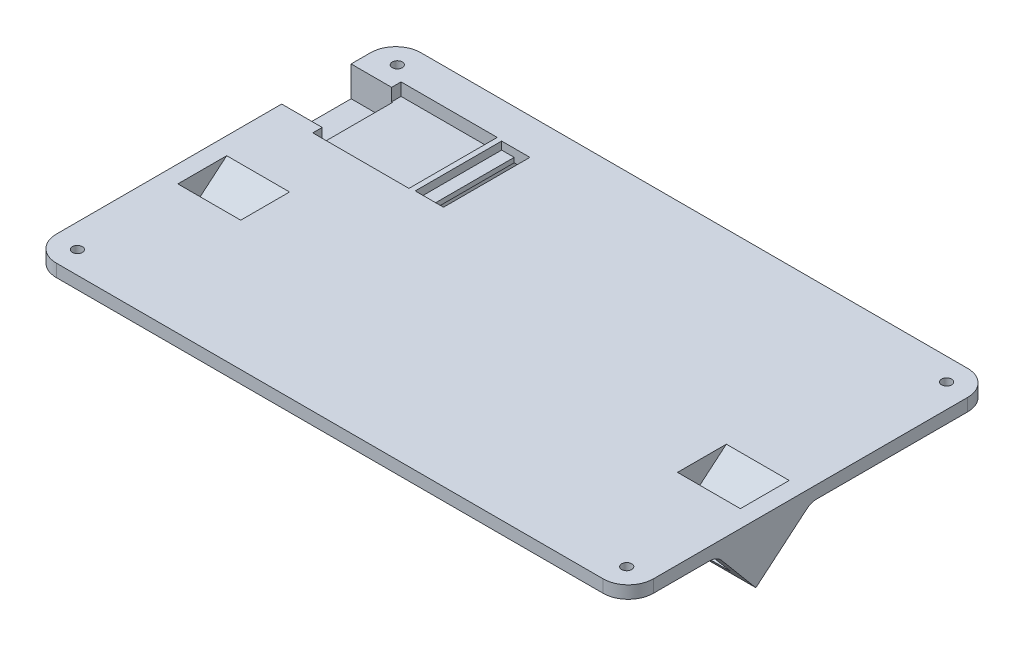
SolidWorks part; units mm, degrees
ref_plane "前视基准面" through (0, 0, 0) normal (0, 0, 1) x (1, 0, 0)
ref_plane "上视基准面" through (0, 0, 0) normal (0, 1, 0) x (1, 0, 0)
ref_plane "右视基准面" through (0, 0, 0) normal (1, 0, 0) x (0, 0, -1)
other "Configuration Table"
sketch "草图1" plane through (0, 0, 0) normal (0, 1, 0) x (1, 0, 0)
  line L1 (-136.2665, -68.2938) -> (136.2665, -68.2938)
  line L2 (-136.2665, -68.2938) -> (-136.2665, 68.2938)
  line L3 (-136.2665, 68.2938) -> (136.2665, 68.2938)
  line L4 (136.2665, -68.2938) -> (136.2665, 68.2938)
  line L5 (-136.2665, -68.2938) -> (136.2665, 68.2938) construction
  line L6 (-136.2665, 68.2938) -> (136.2665, -68.2938) construction
  point P0 (0, 0)
extrude "凸台-拉伸1" add sketch "草图1" along normal blind 4
sketch "草图2" plane through (0, 4, 0) normal (0, 1, 0) x (1, 0, 0)
  line L4 (-87, 58) -> (87, 58) construction
  line L5 (-87, 58) -> (87, 58)
  line L6 (-95, 50) -> (-95, -50)
  line L7 (-87, -58) -> (87, -58)
  line L8 (95, 50) -> (95, -50)
  line L9 (-95, -50) -> (-95, 50) construction
  line L10 (-87, -58) -> (87, -58) construction
  line L11 (95, -50) -> (95, 50) construction
  line L13 (-136.2665, 68.2938) -> (136.2665, 68.2938)
  line L14 (-136.2665, 68.2938) -> (-136.2665, -68.2938)
  line L15 (-136.2665, -68.2938) -> (136.2665, -68.2938)
  line L16 (136.2665, 68.2938) -> (136.2665, -68.2938)
  arc A0 (87, 58) -> (95, 50) centre (87, 50) cw
  arc A1 (-95, -50) -> (-87, -58) centre (-87, -50) ccw
  arc A2 (87, -58) -> (95, -50) centre (87, -50) ccw
  arc A3 (-87, 58) -> (-95, 50) centre (-87, 50) ccw
  dimension "D1" = 8
extrude "切除-拉伸1" cut sketch "草图2" against normal blind 4
sketch "草图3" plane through (0, 0, 0) normal (0, -1, 0) x (1, 0, 0)
  line L0 (-95, -22) -> (-81.8, -22)
  line L1 (-81.8, -22) -> (-81.8, -19)
  line L2 (-81.8, -19) -> (-51.8, -19)
  line L3 (-51.8, -19) -> (-81.8, -19) construction
  line L4 (-51.8, -19) -> (-51.8, -46.5)
  line L5 (-51.8, -46.5) -> (-51.8, -19) construction
  line L6 (-51.8, -46.5) -> (-81.8, -46.5)
  line L7 (-81.8, -46.5) -> (-81.8, -43.5)
  line L8 (-81.8, -43.5) -> (-81.8, -46.5) construction
  line L9 (-81.8, -43.5) -> (-81.8, -22) construction
  line L10 (-81.8, -43.5) -> (-95, -43.5)
  line L11 (-95, -43.5) -> (-95, -22)
extrude "切除-拉伸2" cut sketch "草图3" against normal blind 4
sketch "草图4" plane through (0, 0, 0) normal (0, -1, 0) x (1, 0, 0)
  line L0 (-95, -32.75) -> (-24.4506, -32.75) construction
  line L1 (-95, -43.5) -> (-95, -22) construction
  line L2 (-51.5, -18.7) -> (-51.5, -46.8)
  line L3 (-95, -21.7) -> (-95, -43.8)
  line L4 (-95, -22) -> (-81.8, -22) construction
  line L5 (-81.8, -22) -> (-81.8, -19) construction
  line L6 (-81.8, -19) -> (-51.8, -19) construction
  line L7 (-51.8, -19) -> (-51.8, -46.5) construction
  line L8 (-82.1, -46.8) -> (-51.5, -46.8)
  line L9 (-82.1, -43.8) -> (-82.1, -46.8)
  line L10 (-95, -43.8) -> (-82.1, -43.8)
  line L25 (-95, -21.7) -> (-82.1, -21.7)
  line L26 (-95, -22) -> (-95, 50) construction
  line L27 (-82.1, -21.7) -> (-82.1, -18.7)
  line L28 (-82.1, -18.7) -> (-51.5, -18.7)
  point P19 (-51.5, -32.75)
  dimension "D1" = 0.3
  dimension "D2" = 0.3
  dimension "D3" = 0.3
  dimension "D4" = 0.3
extrude "切除-拉伸3" cut sketch "草图4" against normal blind 4 contours L28 L2 L8 L9 L10 L3 L25 L27
sketch "草图5" plane through (0, 0, 0) normal (0, -1, 0) x (1, 0, 0)
  line L0 (-81.8, -43.5) -> (-81.8, -22) construction
  line L1 (-47.8, -50.75) -> (-81.8, -50.75)
  line L2 (-47.8, -50.75) -> (-47.8, -14.75)
  line L3 (-47.8, -14.75) -> (-81.8, -14.75)
  line L4 (-81.8, -50.75) -> (-81.8, -14.75)
  line L5 (-47.8, -50.75) -> (-81.8, -14.75) construction
  line L6 (-47.8, -14.75) -> (-81.8, -50.75) construction
  line L7 (-95, -32.75) -> (-25.646, -32.75) construction
  line L8 (-95, -22) -> (-95, -43.5) construction
  line L9 (-51.8, -46.5) -> (-51.8, -19) construction
  point P0 (-64.8, -32.75)
  dimension "D1" = 36
  dimension "D2" = 4
extrude "凸台-拉伸2" add sketch "草图5" along normal blind 4 contours L3 L4 L1 L2
sketch "草图6" plane through (0, 0, 0) normal (0, -1, 0) x (1, 0, 0)
  line L0 (-81.8, -18.7) -> (-81.8, -14.75) construction
  line L9 (-95, -21.7) -> (-81.8, -21.7)
  line L10 (-95, -21.7) -> (-95, -17.7)
  line L11 (-95, -17.7) -> (-81.8, -17.7)
  line L12 (-81.8, -21.7) -> (-81.8, -17.7)
  line L13 (-81.8, -50.75) -> (-81.8, -46.8) construction
  line L14 (-95, -43.8) -> (-81.8, -43.8)
  line L15 (-95, -43.8) -> (-95, -47.8)
  line L16 (-95, -47.8) -> (-81.8, -47.8)
  line L17 (-81.8, -43.8) -> (-81.8, -47.8)
  dimension "D1" = 4
  dimension "D2" = 4
extrude "凸台-拉伸3" add sketch "草图6" along normal blind 5.6
sketch "草图7" plane through (0, -5.6, 0) normal (0, -1, 0) x (1, 0, 0)
  line L0 (-95, -47.8) -> (-81.8, -47.8) construction
  line L5 (-95, -17.7) -> (-77.8, -17.7)
  line L6 (-95, -17.7) -> (-95, -47.8)
  line L7 (-95, -47.8) -> (-77.8, -47.8)
  line L8 (-77.8, -17.7) -> (-77.8, -47.8)
  line L9 (-81.8, -43.5) -> (-81.8, -22) construction
  dimension "D1" = 4
extrude "凸台-拉伸4" add sketch "草图7" along normal blind 4
sketch "草图8" plane through (0, 4, 0) normal (0, 1, 0) x (1, 0, 0)
  line L1 (-81.8, 19) -> (-45.8, 19) construction
  line L2 (-45.8, 46.5) -> (-40.8, 46.5)
  line L3 (-45.8, 46.5) -> (-45.8, 19)
  line L4 (-45.8, 19) -> (-40.8, 19)
  line L5 (-40.8, 46.5) -> (-40.8, 19)
  dimension "D1" = 5
extrude "切除-拉伸4" cut sketch "草图8" against normal blind 4
sketch "草图9" plane through (-45.8, 0, 0) normal (1, 0, 0) x (0, 0, -1)
  line L0 (19, -0.1) -> (19, 6.4) construction
  line L1 (19, 4) -> (46.5, 4)
  line L2 (19, 4) -> (19, 1.5)
  line L3 (19, 1.5) -> (46.5, 1.5)
  line L4 (46.5, 4) -> (46.5, 1.5)
  line L5 (7.5, 4) -> (21.5, 4) construction
  line L6 (46.5, 6.4) -> (46.5, 7.9) construction
  dimension "D1" = 2.5
extrude "切除-拉伸5" cut sketch "草图9" against normal blind 4
sketch "草图10" plane through (0, 4, 0) normal (0, 1, 0) x (1, 0, 0)
  circle A0 centre (87.4, 50.9) radius 1.6
  circle A1 centre (-87.4, 50.9) radius 1.6
  circle A2 centre (-87.4, -50.9) radius 1.6
  circle A3 centre (87.4, -50.9) radius 1.6
extrude "切除-拉伸6" cut sketch "草图10" against normal blind 10
sketch "草图11" plane through (95, 0, 0) normal (1, 0, 0) x (0, 0, -1)
  line L0 (0.1985, 0.0243) -> (-29.8015, 0)
  line L1 (-50, 0) -> (50, 0) construction
  line L2 (-29.8015, 0) -> (-17.3942, -14.7621)
  line L3 (0.1985, 0.0243) -> (-17.3942, -14.7621)
  dimension "D1" = 50
  dimension "D2" = 30
  dimension "D3" = 90
  dimension "D4" = 12.4073
extrude "凸台-拉伸5" add sketch "草图11" against normal up to surface (190 mm away) up to face at (-95, -1.2, -21.8333)
sketch "草图13" plane through (0, -14.6785, 17.4644) normal (0, -0.6434, 0.7655) x (1, 0, 0)
  line L0 (95, 19.1745) -> (95, -0.1091) construction
  line L1 (89.5, 3.8909) -> (69.5, 3.8909)
  line L2 (89.5, 3.8909) -> (89.5, 13.8909)
  line L3 (89.5, 13.8909) -> (69.5, 13.8909)
  line L4 (69.5, 3.8909) -> (69.5, 13.8909)
  line L5 (-95, -0.1091) -> (95, -0.1091) construction
  line L6 (-87, 37.3177) -> (87, 37.3177) construction
  line L7 (0, 37.3177) -> (0, 0) construction
  line L8 (-69.5, 3.8909) -> (-69.5, 13.8909)
  line L9 (-89.5, 13.8909) -> (-69.5, 13.8909)
  line L10 (-89.5, 3.8909) -> (-89.5, 13.8909)
  line L11 (-89.5, 3.8909) -> (-69.5, 3.8909)
  dimension "D1" = 10
  dimension "D2" = 20
  dimension "D3" = 5.5
  dimension "D4" = 4
extrude "切除-拉伸7" cut sketch "草图13" against normal blind 300
sketch "草图16" plane through (0, 0, 0) normal (0, -1, 0) x (1, 0, 0)
  line L0 (-95, -0.1696) -> (95, -0.1696) construction
  line L2 (-61.7314, -12.2197) -> (-61.7314, 32.6069)
  line L3 (-61.7314, 32.6069) -> (61.7314, 32.6069)
  line L4 (61.7314, -12.2197) -> (61.7314, 32.6069)
  line L5 (-22.6953, -12.2197) -> (61.7314, 32.6069) construction
  line L6 (-61.7314, 32.6069) -> (22.6953, -12.2197) construction
  line L7 (-61.7314, -12.2197) -> (61.7314, -12.2197)
  point P0 (0, -0.1696)
extrude "切除-拉伸8" cut sketch "草图16" along normal blind 21
fillet "圆角2" radius 5 6 edges at (-78.3657, 0, -0.1696) (-61.7314, 0, 14.816) (-78.3657, 0, 29.8015) (78.3657, 0, 29.8015) (78.3657, 0, -0.1696) (61.7314, 0, 14.816)
